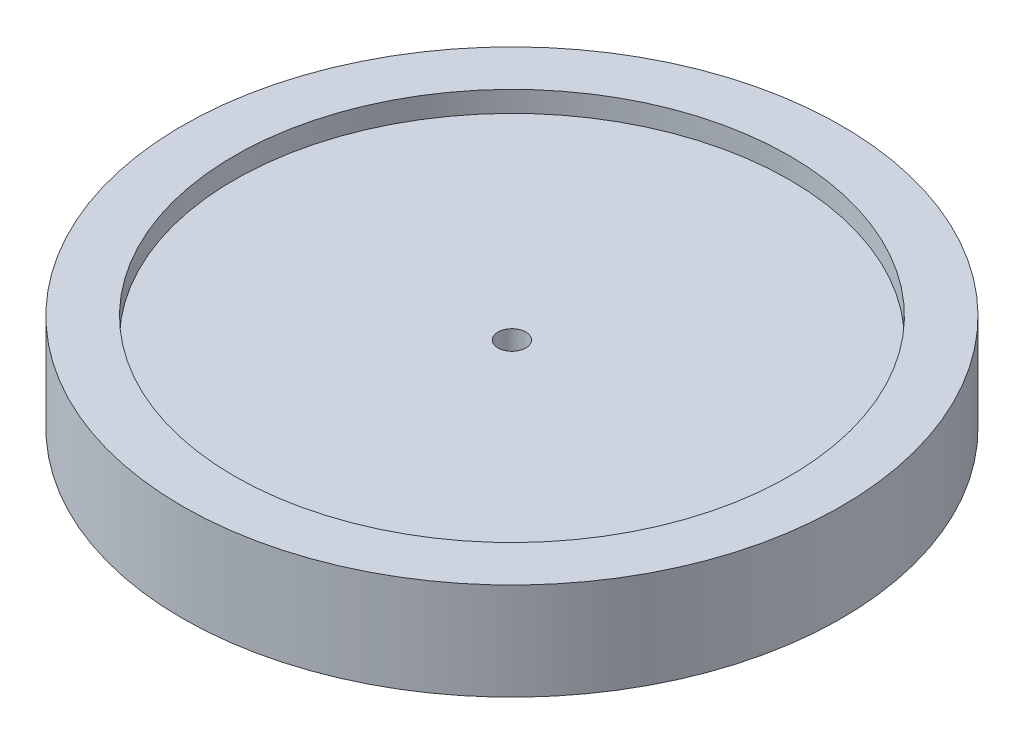
SolidWorks part; units mm, degrees
ref_plane "前视基准面" through (0, 0, 0) normal (0, 0, 1) x (1, 0, 0)
ref_plane "上视基准面" through (0, 0, 0) normal (0, 1, 0) x (1, 0, 0)
ref_plane "右视基准面" through (0, 0, 0) normal (1, 0, 0) x (0, 0, -1)
sketch "草图1" plane through (0, 0, 0) normal (0, 1, 0) x (1, 0, 0)
  circle A0 centre (0, 0) radius 2
  circle A1 centre (0, 0) radius 47.5
  dimension "D1" = 4
  dimension "D2" = 95
extrude "凸台-拉伸1" add sketch "草图1" along normal blind 14
ref_plane "基准面1" through (0, 0, 0) normal (0, -1, 0) x (-1, 0, 0)
sketch "草图2" plane through (0, 0, 0) normal (0, -1, 0) x (-1, 0, 0)
  circle A0 centre (0, 0) radius 9
  circle A1 centre (0, 0) radius 2
extrude "凸台-拉伸2" add sketch "草图2" along normal blind 5.2
ref_plane "基准面2" through (0, 14, 0) normal (0, 1, 0) x (1, 0, 0)
sketch "草图3" plane through (0, 14, 0) normal (0, 1, 0) x (1, 0, 0)
  circle A0 centre (0, 0) radius 40
  dimension "D1" = 80
sketch "草图4" plane through (0, 0, 0) normal (0, -1, 0) x (1, 0, 0)
  circle A0 centre (0, 0) radius 40
  circle A1 centre (0, 0) radius 9
  dimension "D1" = 80
extrude "切除-拉伸3" cut sketch "草图4" against normal blind 3
extrude "切除-拉伸4" cut sketch "草图3" against normal blind 3
